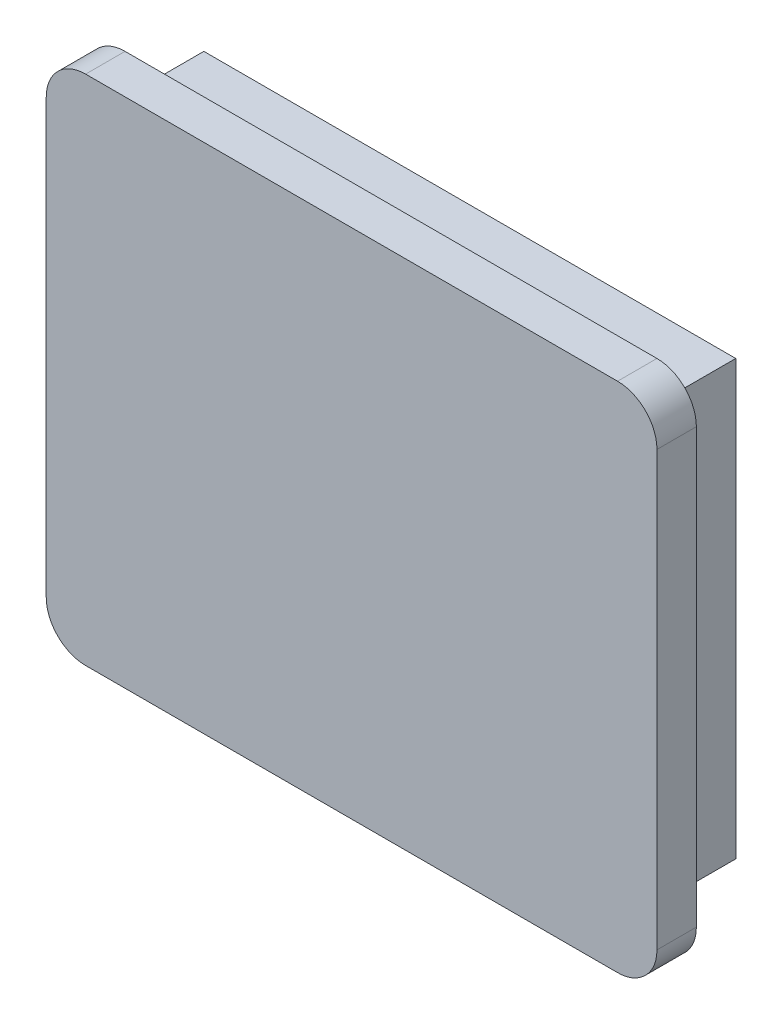
SolidWorks part; units mm, degrees
ref_plane "Plan de face" through (0, 0, 0) normal (0, 0, 1) x (1, 0, 0)
ref_plane "Plan de dessus" through (0, 0, 0) normal (0, 1, 0) x (1, 0, 0)
ref_plane "Plan de droite" through (0, 0, 0) normal (1, 0, 0) x (0, 0, -1)
sketch "Esquisse1" plane through (0, 0, 0) normal (0, 0, 1) x (1, 0, 0)
  line L1 (-7.75, -6.5) -> (7.75, -6.5)
  line L2 (-7.75, -6.5) -> (-7.75, 6.5)
  line L3 (-7.75, 6.5) -> (7.75, 6.5)
  line L4 (7.75, -6.5) -> (7.75, 6.5)
  line L5 (6.75, 5.5) -> (-6.75, 5.5)
  line L6 (6.75, 5.5) -> (6.75, -5.5)
  line L7 (6.75, -5.5) -> (-6.75, -5.5)
  line L8 (-6.75, 5.5) -> (-6.75, -5.5)
  line L9 (6.75, 5.5) -> (-6.75, -5.5) construction
  line L10 (6.75, -5.5) -> (-6.75, 5.5) construction
  point P6 (0, 0)
  dimension "D1" = 1
  dimension "D2" = 1
  dimension "D3" = 1
  dimension "D4" = 1
sketch "Esquisse2" plane through (0, 0, 0) normal (0, 0, 1) x (1, 0, 0)
  line L1 (7.75, -6.5) -> (-7.75, -6.5)
  line L2 (7.75, -6.5) -> (7.75, 6.5)
  line L3 (7.75, 6.5) -> (-7.75, 6.5)
  line L4 (-7.75, -6.5) -> (-7.75, 6.5)
  line L5 (7.75, -6.5) -> (-7.75, 6.5) construction
  line L6 (7.75, 6.5) -> (-7.75, -6.5) construction
  point P0 (0, 0)
extrude "Boss.-Extru.1" add sketch "Esquisse2" along normal blind 1
sketch "Esquisse3" plane through (0, 0, 0) normal (0, 0, -1) x (-1, 0, 0)
  line L0 (5.5227, -4.5) -> (6.75, -4.5)
  line L1 (6.75, -5.5) -> (-6.75, -5.5)
  line L2 (6.75, -5.5) -> (6.75, -4.5)
  line L3 (6.75, 5.5) -> (-6.75, 5.5)
  line L4 (-6.75, -5.5) -> (-6.75, 5.5)
  line L5 (6.75, -5.5) -> (-6.75, 5.5) construction
  line L6 (6.75, 5.5) -> (-6.75, -5.5) construction
  line L7 (5.5227, -4.5) -> (-5.5227, -4.5)
  line L9 (5.5227, 4.5) -> (-5.5227, 4.5)
  line L10 (-5.5227, -4.5) -> (-5.5227, 4.5)
  line L11 (5.5227, -4.5) -> (-5.5227, 4.5) construction
  line L12 (5.5227, 4.5) -> (-5.5227, -4.5) construction
  line L13 (5.5227, 4.5) -> (6.75, 4.5)
  line L14 (6.75, 4.5) -> (6.75, 5.5)
  point P0 (0, 0)
  point P7 (0, 0)
  dimension "D1" = 1
extrude "Boss.-Extru.2" add sketch "Esquisse3" along normal blind 2
fillet "Congé1" radius 1 4 edges at (7.75, -6.5, 0.5) (-7.75, -6.5, 0.5) (-7.75, 6.5, 0.5) (7.75, 6.5, 0.5)
